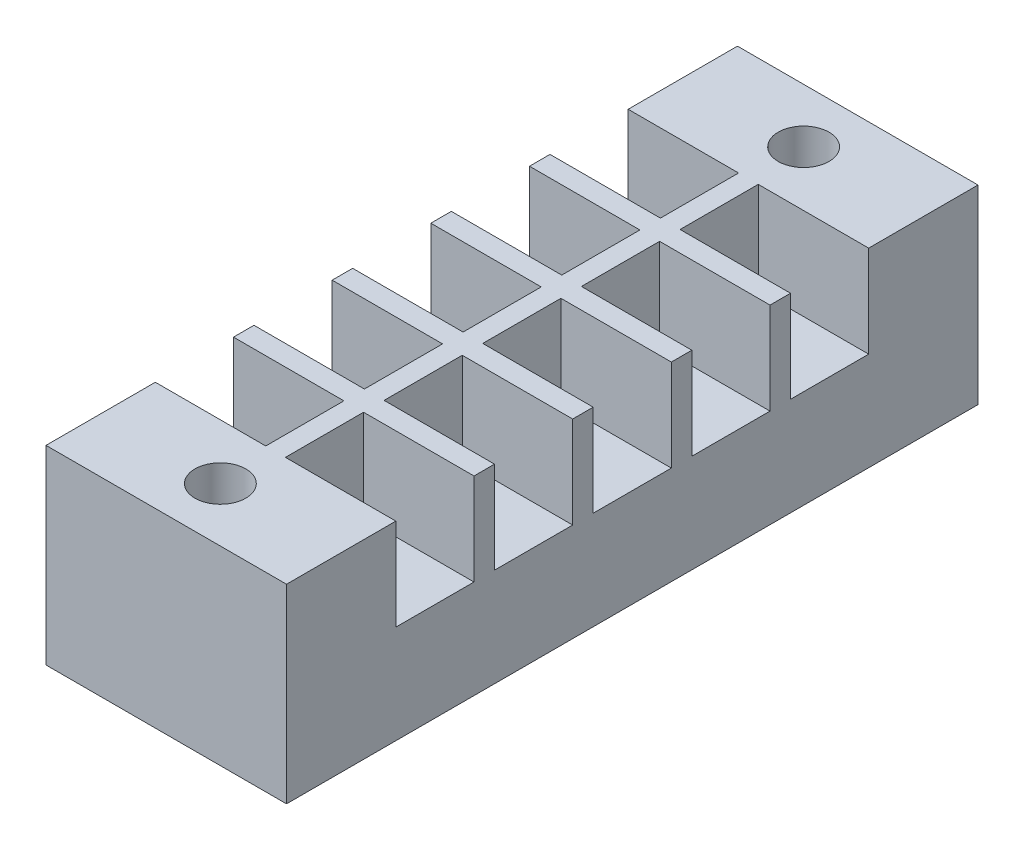
SolidWorks part; units mm, degrees
material "ABS"
ref_plane "Front Plane" through (0, 0, 0) normal (0, 0, 1) x (1, 0, 0)
ref_plane "Top Plane" through (0, 0, 0) normal (0, 1, 0) x (1, 0, 0)
ref_plane "Right Plane" through (0, 0, 0) normal (1, 0, 0) x (0, 0, -1)
sketch "Sketch1" plane through (0, 0, 0) normal (0, 1, 0) x (1, 0, 0)
  line L1 (-11, 31.625) -> (11, 31.625)
  line L2 (-11, 31.625) -> (-11, -31.625)
  line L3 (-11, -31.625) -> (11, -31.625)
  line L4 (11, 31.625) -> (11, -31.625)
  line L5 (-11, 31.625) -> (11, -31.625) construction
  line L6 (-11, -31.625) -> (11, 31.625) construction
  point P0 (0, 0)
  dimension "D1" = 63.25
  dimension "D2" = 22
extrude "Boss-Extrude1" add sketch "Sketch1" along normal blind 17.4
sketch "Sketch2" plane through (0, 17.4, 0) normal (0, 1, 0) x (1, 0, 0)
  line L0 (-11, 31.625) -> (-11, -31.625) construction
  line L1 (-11, 21.625) -> (-0.9, 21.625)
  line L2 (-11, 21.625) -> (-11, 14.475)
  line L3 (-11, 14.475) -> (-0.9, 14.475)
  line L4 (-0.9, 21.625) -> (-0.9, 14.475)
  line L5 (11, -31.625) -> (11, 31.625) construction
  line L6 (11, 14.475) -> (0.9, 14.475)
  line L7 (11, 14.475) -> (11, 21.625)
  line L8 (11, 21.625) -> (0.9, 21.625)
  line L9 (0.9, 14.475) -> (0.9, 21.625)
  line L10 (11, 31.625) -> (-11, 31.625) construction
  line L11 (-11, 12.6) -> (-0.9, 12.6)
  line L12 (-11, 12.6) -> (-11, 5.45)
  line L13 (-11, 5.45) -> (-0.9, 5.45)
  line L14 (-0.9, 12.6) -> (-0.9, 5.45)
  line L15 (11, 5.45) -> (0.9, 5.45)
  line L16 (11, 5.45) -> (11, 12.6)
  line L17 (11, 12.6) -> (0.9, 12.6)
  line L18 (0.9, 5.45) -> (0.9, 12.6)
  line L19 (-11, 3.575) -> (-0.9, 3.575)
  line L20 (-11, 3.575) -> (-11, -3.575)
  line L21 (-11, -3.575) -> (-0.9, -3.575)
  line L22 (-0.9, 3.575) -> (-0.9, -3.575)
  line L23 (11, -3.575) -> (0.9, -3.575)
  line L24 (11, -3.575) -> (11, 3.575)
  line L25 (11, 3.575) -> (0.9, 3.575)
  line L26 (0.9, -3.575) -> (0.9, 3.575)
  line L27 (-11, -5.45) -> (-0.9, -5.45)
  line L28 (-11, -5.45) -> (-11, -12.6)
  line L29 (-11, -12.6) -> (-0.9, -12.6)
  line L30 (-0.9, -5.45) -> (-0.9, -12.6)
  line L31 (11, -12.6) -> (0.9, -12.6)
  line L32 (11, -12.6) -> (11, -5.45)
  line L33 (11, -5.45) -> (0.9, -5.45)
  line L34 (0.9, -12.6) -> (0.9, -5.45)
  line L35 (-11, -14.475) -> (-0.9, -14.475)
  line L36 (-11, -14.475) -> (-11, -21.625)
  line L37 (-11, -21.625) -> (-0.9, -21.625)
  line L38 (-0.9, -14.475) -> (-0.9, -21.625)
  line L39 (11, -21.625) -> (0.9, -21.625)
  line L40 (11, -21.625) -> (11, -14.475)
  line L41 (11, -14.475) -> (0.9, -14.475)
  line L42 (0.9, -21.625) -> (0.9, -14.475)
  line L43 (-11, -31.625) -> (11, -31.625) construction
  dimension "D1" = 7.15
  dimension "D2" = 10
  dimension "D3" = 1.8
  dimension "D5" = 10
  dimension "D4" = 5
extrude "Cut-Extrude1" cut sketch "Sketch2" against normal blind 8.4
sketch "Sketch3" plane through (0, 0, 0) normal (0, 1, 0) x (1, 0, 0)
  line L0 (0, -26.675) -> (0, 26.675) construction
  circle A0 centre (0, 26.675) radius 2.325
  circle A1 centre (0, -26.675) radius 2.325
  dimension "D1" = 4.65
  dimension "D2" = 53.35
extrude "Cut-Extrude2" cut sketch "Sketch3" along normal through all
